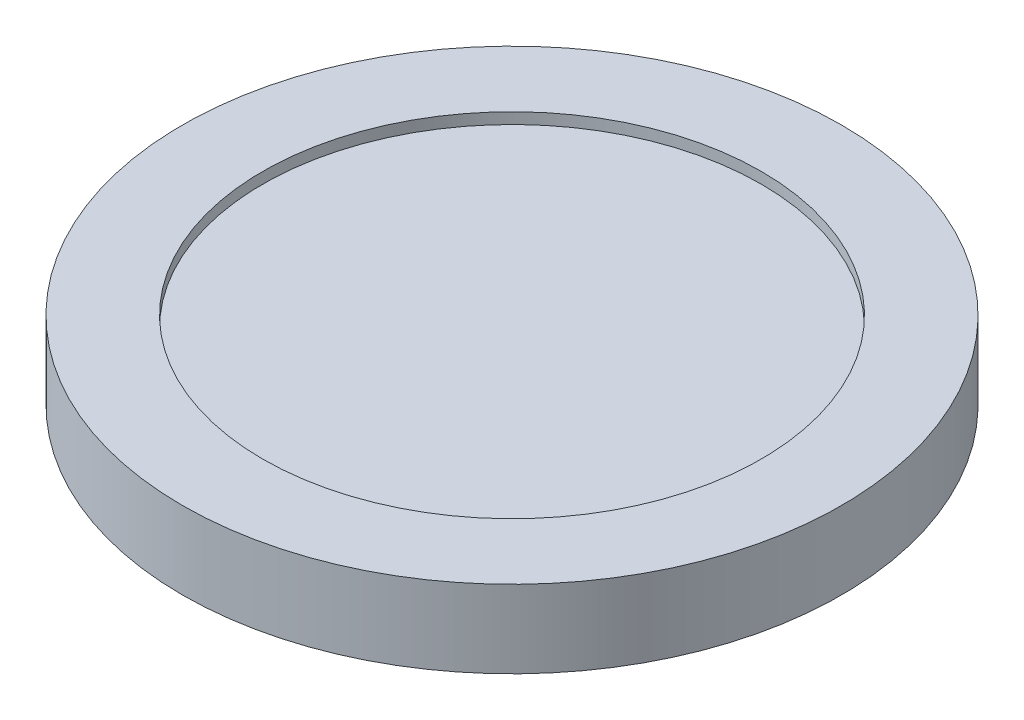
SolidWorks part; units mm, degrees
ref_plane "前视基准面" through (0, 0, 0) normal (0, 0, 1) x (1, 0, 0)
ref_plane "上视基准面" through (0, 0, 0) normal (0, 1, 0) x (1, 0, 0)
ref_plane "右视基准面" through (0, 0, 0) normal (1, 0, 0) x (0, 0, -1)
other "Configuration Table"
sketch "草图1" plane through (0, 0, 0) normal (0, 1, 0) x (1, 0, 0)
  circle A0 centre (0, 0) radius 11.9
  dimension "D1" = 23.8
extrude "凸台-拉伸1" add sketch "草图1" along normal blind 2.8
sketch "草图2" plane through (0, 2.8, 0) normal (0, 1, 0) x (1, 0, 0)
  circle A0 centre (0, 0) radius 9
  dimension "D1" = 18
extrude "切除-拉伸1" cut sketch "草图2" against normal blind 0.4
